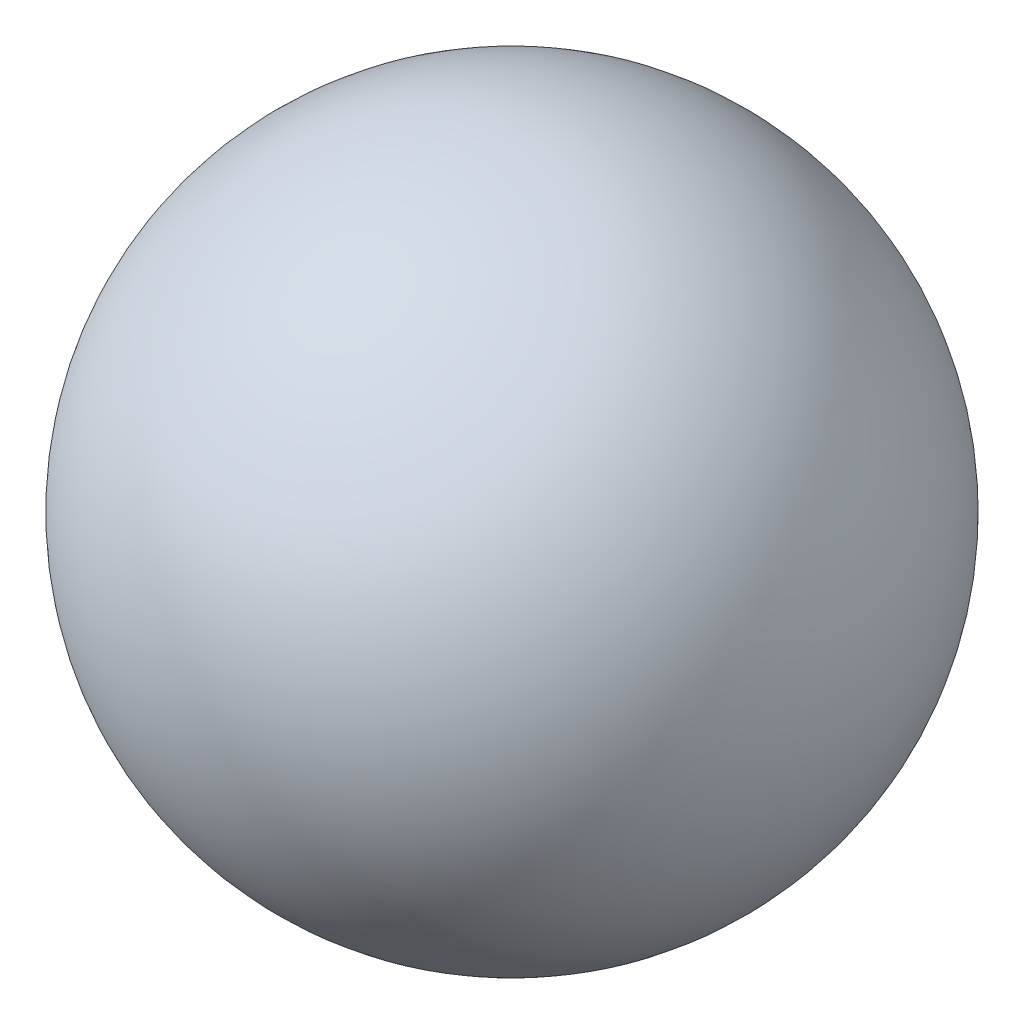
SolidWorks part; units mm, degrees
ref_plane "Front" through (0, 0, 0) normal (0, 0, 1) x (1, 0, 0)
ref_plane "Top" through (0, 0, 0) normal (0, 1, 0) x (1, 0, 0)
ref_plane "Right" through (0, 0, 0) normal (1, 0, 0) x (0, 0, -1)
sketch "Sketch1" plane through (0, 0, 0) normal (0, 0, 1) x (1, 0, 0)
  line L3 (0, 0) -> (0, 25.4) construction
  line L4 (0, 25.4) -> (0, 0)
  arc A1 (0, 25.4) -> (0, 0) centre (0, 12.7) cw
  dimension "D2" = 25.4
revolve "Revolve1" add sketch "Sketch1" angle 360 about L3
